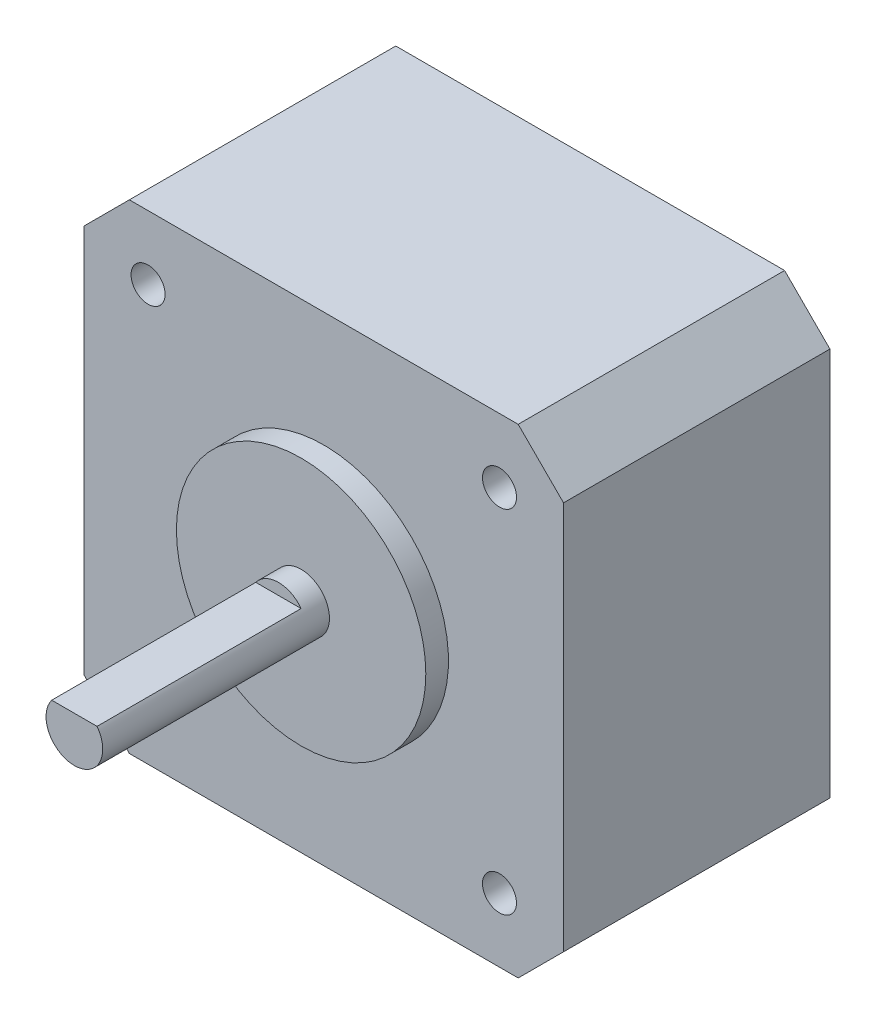
SolidWorks part; units mm, degrees
ref_plane "Front Plane" through (0, 0, 0) normal (0, 0, 1) x (1, 0, 0)
ref_plane "Top Plane" through (0, 0, 0) normal (0, 1, 0) x (1, 0, 0)
ref_plane "Right Plane" through (0, 0, 0) normal (1, 0, 0) x (0, 0, -1)
sketch "Sketch1" plane through (0, 0, 0) normal (0, 0, 1) x (1, 0, 0)
  line L0 (0, 21.15) -> (0, -21.15) construction
  line L1 (-17.15, -21.15) -> (17.15, -21.15)
  line L2 (-21.15, -17.15) -> (-21.15, 17.15)
  line L3 (-17.15, 21.15) -> (17.15, 21.15)
  line L4 (21.15, -17.15) -> (21.15, 17.15)
  line L5 (-21.15, -21.15) -> (21.15, 21.15) construction
  line L6 (-21.15, 21.15) -> (21.15, -21.15) construction
  line L8 (15.5, 0) -> (-15.5, 0) construction
  line L9 (-15.5, 15.5) -> (-15.5, -15.5) construction
  line L10 (15.5, 15.5) -> (15.5, -15.5) construction
  line L11 (-21.15, 17.15) -> (-17.15, 21.15)
  line L12 (17.15, 21.15) -> (21.15, 17.15)
  line L13 (-21.15, -17.15) -> (-17.15, -21.15)
  line L14 (17.15, -21.15) -> (21.15, -17.15)
  circle A0 centre (-15.5, 15.5) radius 1.5
  circle A1 centre (15.5, 15.5) radius 1.5
  circle A2 centre (15.5, -15.5) radius 1.5
  circle A3 centre (-15.5, -15.5) radius 1.5
  point P0 (0, 0)
  point P13 (0, 0)
  point P16 (-15.5, 0)
  point P30 (0, 0)
  point P31 (36.1638, 21.15)
  point P32 (0, 0)
  point P33 (0, 21.15)
  point P34 (-23.993, 0)
  point P35 (0, 0)
  dimension "D7" = 3
  dimension "D1" = 42.3
  dimension "D2" = 42.3
  dimension "D3" = 31
  dimension "D4" = 31
  dimension "D5" = 2
  dimension "D6" = 2
extrude "Boss-Extrude1" add sketch "Sketch1" along normal blind 23.5
sketch "Sketch2" plane through (0, -21.15, 0) normal (0, -1, 0) x (1, 0, 0)
  line L0 (-17.15, 0) -> (17.15, 0) construction
  line L1 (-8.1, 0) -> (8.1, 0)
  line L2 (-8.1, 0) -> (-8.1, 9.2)
  line L3 (-8.1, 9.2) -> (8.1, 9.2)
  line L4 (8.1, 0) -> (8.1, 9.2)
  point P6 (23.0936, 9.2)
  point P7 (0, 0)
  dimension "D1" = 16.2
  dimension "D2" = 9.2
extrude "Boss-Extrude2" add sketch "Sketch2" along normal blind 5.5
sketch "Sketch3" plane through (0, 0, 23.5) normal (0, 0, 1) x (1, 0, 0)
  circle A0 centre (0, 0) radius 11
  dimension "D1" = 22
extrude "Boss-Extrude3" add sketch "Sketch3" along normal blind 2
sketch "Sketch4" plane through (0, 0, 25.5) normal (0, 0, 1) x (1, 0, 0)
  circle A0 centre (0, 0) radius 2.5
  dimension "D1" = 5
extrude "Boss-Extrude4" add sketch "Sketch4" along normal blind 20
ref_plane "Plane1" through (0, 2.5, 0) normal (0, 1, 0) x (1, 0, 0)
sketch "Sketch5" plane through (0, 2.5, 0) normal (0, 1, 0) x (1, 0, 0)
  line L0 (-2.5, -25.5) -> (-2.5, -45.5) construction
  line L1 (2.5, -45.5) -> (-2.5, -45.5)
  line L2 (2.5, -45.5) -> (2.5, -27.5)
  line L3 (2.5, -27.5) -> (-2.5, -27.5)
  line L4 (-2.5, -45.5) -> (-2.5, -27.5)
  dimension "D1" = 18
extrude "Cut-Extrude1" cut sketch "Sketch5" against normal blind 1
